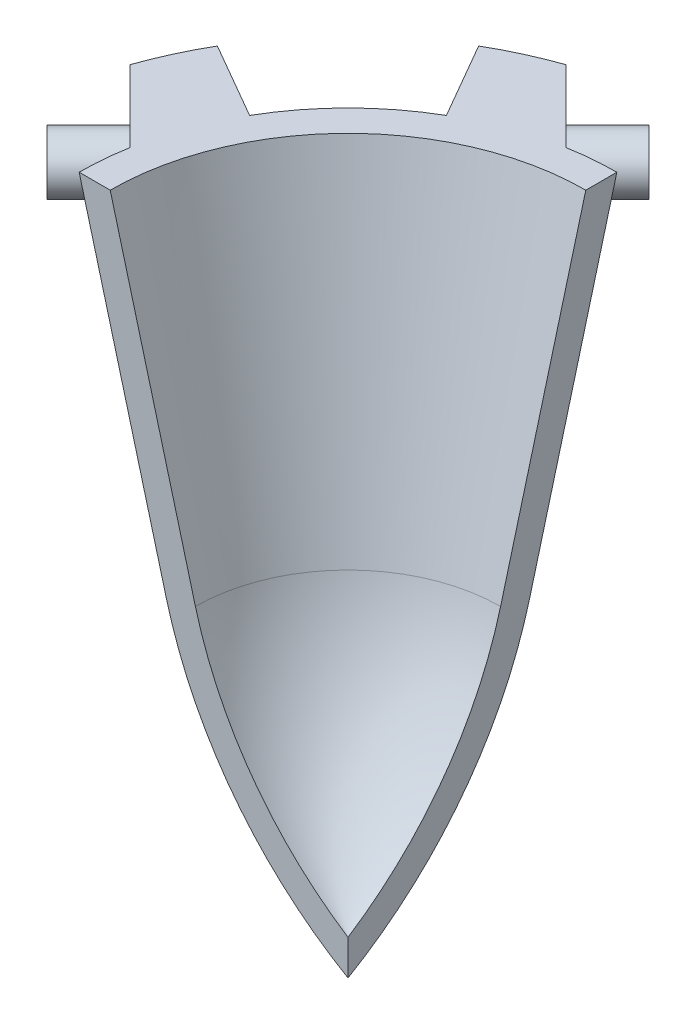
SolidWorks part; units mm, degrees
ref_plane "Alzado" through (0, 0, 0) normal (0, 0, 1) x (1, 0, 0)
ref_plane "Planta" through (0, 0, 0) normal (0, 1, 0) x (1, 0, 0)
ref_plane "Vista lateral" through (0, 0, 0) normal (1, 0, 0) x (0, 0, -1)
sketch "Croquis2" plane through (0, 0, 0) normal (1, 0, 0) x (0, 0, -1)
  line L0 (0, 0) -> (0, 6)
  line L1 (26, 41.82) -> (40.5175, 96)
  line L2 (40.5175, 96) -> (45.8068, 96)
  line L3 (45.8068, 96) -> (30.935, 40.4977)
  line L4 (0, 0) -> (0, 47.1812) construction
  arc A0 (0, 6) -> (26, 41.82) centre (-33.7203, 57.822) ccw
  arc A1 (30.935, 40.4977) -> (0, 0) centre (-33.7203, 57.822) cw
  dimension "D1" = 90
  dimension "D2" = 6
  dimension "D3" = 15
  dimension "D4" = 35.82
  dimension "D5" = 26
revolve "Revolución1" add sketch "Croquis2" angle 90 about L4
sketch "Croquis9" plane through (0, 0, 0) normal (1, 0, 0) x (0, 0, -1)
  line L0 (0, 0) -> (0, 71.7419) construction
  line L1 (0, 96) -> (0, 41.82) construction
ref_plane "Plano1" through (0, 0, 0) normal (0.866, 0, -0.5) x (0, 1, 0)
ref_plane "Plano2" through (0, 0, 0) normal (0.5, 0, -0.866) x (0, 1, 0)
sketch "Croquis10" plane through (0, 0, 0) normal (0.866, 0, -0.5) x (0, 1, 0)
  line L0 (81, -41.7876) -> (96, -45.8068)
  line L1 (40.4977, -30.935) -> (96, -45.8068) construction
  line L2 (96, -45.8068) -> (96, -60.8068)
  line L3 (96, -60.8068) -> (81, -56.7876)
  line L4 (81, -56.7876) -> (81, -41.7876)
  dimension "D1" = 15
  dimension "D2" = 15
revolve "Revolución2" add sketch "Croquis10" angle 20 about L0
sketch "Croquis11" plane through (0, 0, 0) normal (0.5, 0, -0.866) x (0, 1, 0)
  line L0 (96, -45.8068) -> (96, -60.8068)
  line L1 (96, -52.6603) -> (96, -39.6699) construction
  line L2 (96, -60.8068) -> (81, -56.7876)
  line L3 (81, -56.7876) -> (81, -41.7876)
  line L4 (81, -36.1891) -> (81, -49.1795) construction
  line L5 (40.4977, -30.935) -> (96, -45.8068) construction
  line L6 (81, -41.7876) -> (96, -45.8068)
  dimension "D1" = 15
revolve "Revolución3" add sketch "Croquis11" angle 20 about L0
sketch "Croquis12" plane through (0, 96, 0) normal (0, 1, 0) x (1, 0, 0)
  line L0 (0, 0) -> (-37.2343, 0) construction
  line L1 (-40.5175, 0) -> (-26, 0) construction
  line L2 (0, 0) -> (-35.5507, 35.5507) construction
  line L3 (-7.9543, 45.1109) -> (-20.1977, 57.3544)
  line L4 (-10.559, 59.883) -> (-7.9543, 45.1109)
  line L5 (-45.1109, 7.9543) -> (-57.3544, 20.1977)
  line L6 (-59.883, 10.559) -> (-45.1109, 7.9543)
  arc A0 (-10.559, 59.883) -> (-30.4034, 52.6603) centre (0, 0) ccw construction
  arc A1 (-20.1977, 57.3544) -> (-10.559, 59.883) centre (0, 0) cw
  arc A2 (-57.3544, 20.1977) -> (-59.883, 10.559) centre (0, 0) ccw
  dimension "D1" = 45
extrude "Cortar-Extruir1" cut sketch "Croquis12" against normal through all
sketch "Croquis13" plane through (18.5783, 0, -18.5783) normal (0.7071, 0, -0.7071) x (-0.7071, 0, -0.7071)
  line L1 (43.9334, 81) -> (46.1802, 96) construction
  line L2 (50.344, 81) -> (37.5227, 81) construction
  line L3 (54.8376, 96) -> (37.5227, 96) construction
  circle A0 centre (45.0568, 88.5) radius 4.5
  point P10 (45.0568, 88.5)
  dimension "D1" = 9
extrude "Saliente-Extruir1" add sketch "Croquis13" along normal blind 10
ref_plane "Plano3" through (0, 0, 0) normal (0.7071, 0, -0.7071) x (-0.7071, 0, -0.7071)
mirror "Simetría1" about plane through (0, 0, 0) normal (0.7071, 0, -0.7071) of "Saliente-Extruir1"
